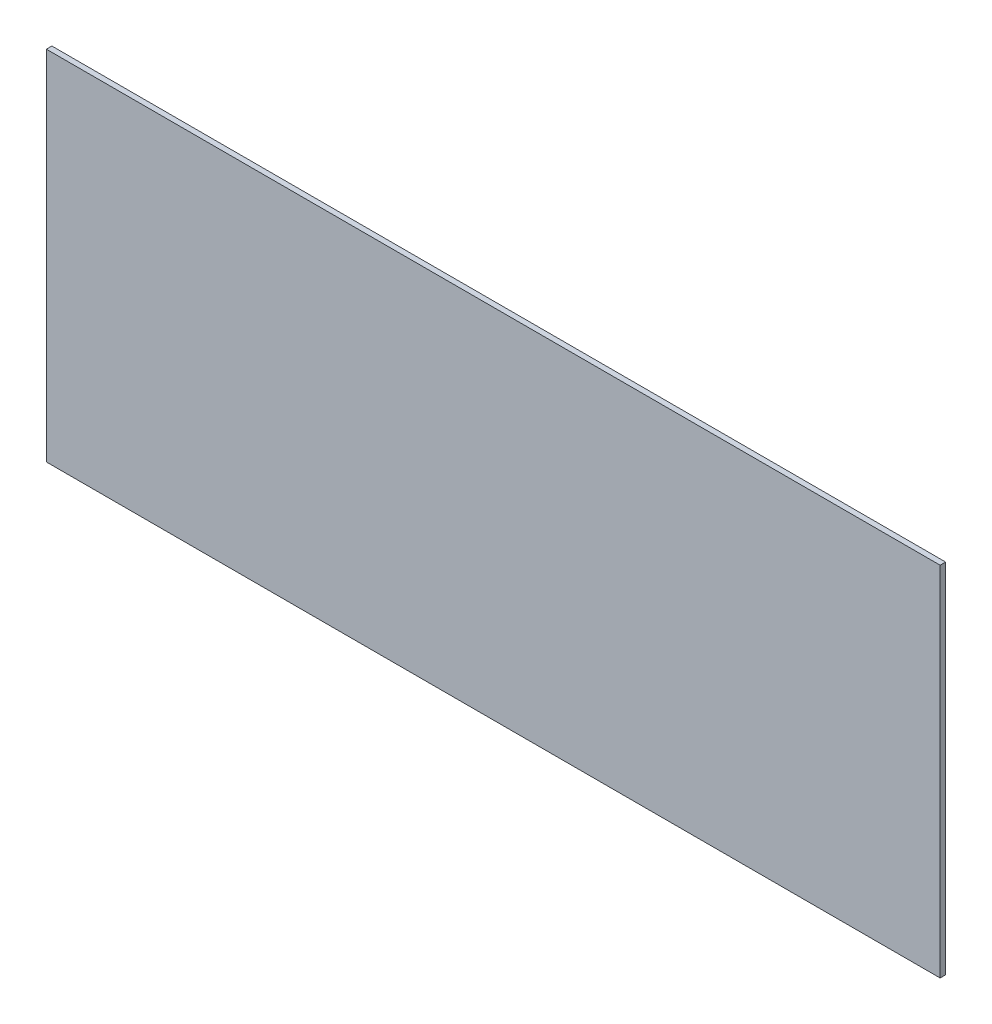
SolidWorks part; units mm, degrees
ref_plane "Front Plane" through (0, 0, 0) normal (0, 0, 1) x (1, 0, 0)
ref_plane "Top Plane" through (0, 0, 0) normal (0, 1, 0) x (1, 0, 0)
ref_plane "Right Plane" through (0, 0, 0) normal (1, 0, 0) x (0, 0, -1)
sketch "Sketch1" plane through (0, 0, 0) normal (0, 0, 1) x (1, 0, 0)
  line L1 (-118.2088, 16.5) -> (11.7912, 16.5)
  line L2 (-118.2088, 16.5) -> (-118.2088, -35.5)
  line L3 (-118.2088, -35.5) -> (11.7912, -35.5)
  line L4 (11.7912, 16.5) -> (11.7912, -35.5)
  dimension "D1" = 52
  dimension "D2" = 130
extrude "Boss-Extrude1" add sketch "Sketch1" along normal blind 0.8
